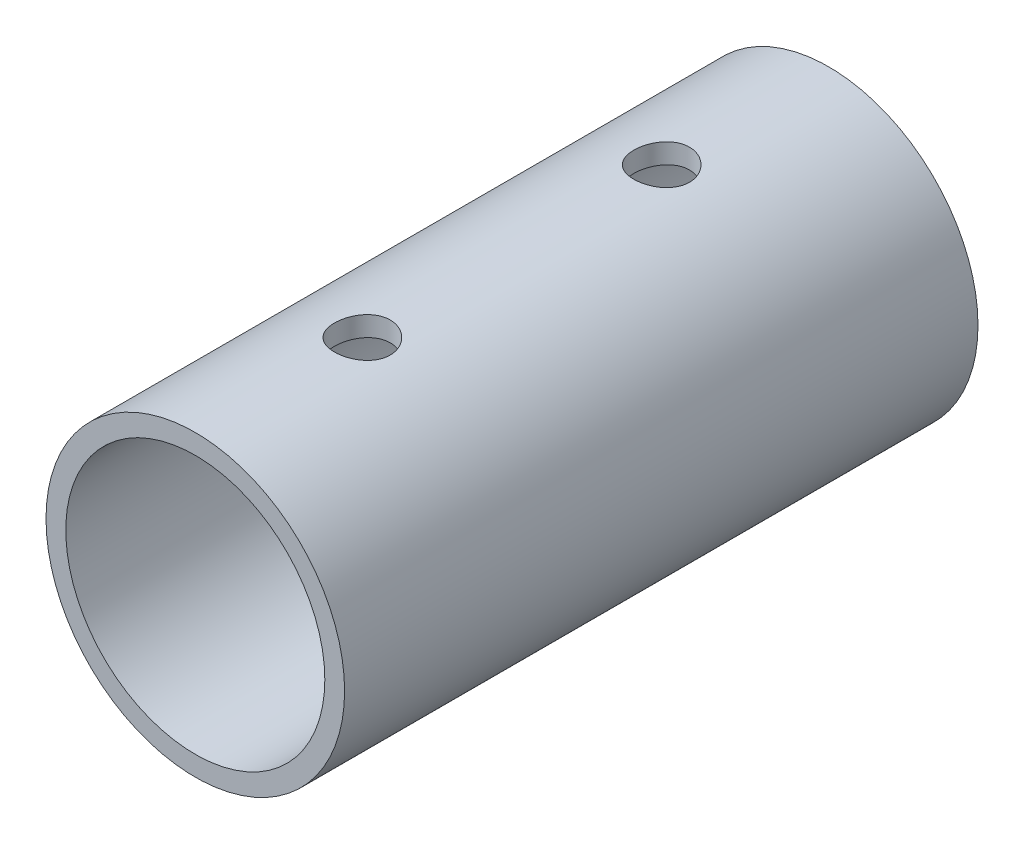
SolidWorks part; units mm, degrees
ref_plane "Front Plane" through (0, 0, 0) normal (0, 0, 1) x (1, 0, 0)
ref_plane "Top Plane" through (0, 0, 0) normal (0, 1, 0) x (1, 0, 0)
ref_plane "Right Plane" through (0, 0, 0) normal (1, 0, 0) x (0, 0, -1)
sketch "Sketch1" plane through (0, 0, 0) normal (0, 0, 1) x (1, 0, 0)
  circle A0 centre (0, 0) radius 14.7701
  circle A1 centre (0, 0) radius 17.0264
extrude "Boss-Extrude1" add sketch "Sketch1" along normal blind 72.2313
ref_plane "Plane1" through (0, 17.0264, 0) normal (0, 1, 0) x (1, 0, 0)
sketch "Sketch2" plane through (0, 17.0264, 0) normal (0, 1, 0) x (1, 0, 0)
  line L0 (0, -72.3326) -> (0, 0) construction
  line L1 (-17.0264, -72.2313) -> (17.0264, -72.2313) construction
  line L2 (17.0264, 0) -> (-17.0264, 0) construction
  circle A0 centre (0, -53.1812) radius 3.175
  circle A1 centre (0, -19.05) radius 3.175
  dimension "D1" = 19.05
  dimension "D2" = 19.05
extrude "Cut-Extrude1" cut sketch "Sketch2" against normal up to next
